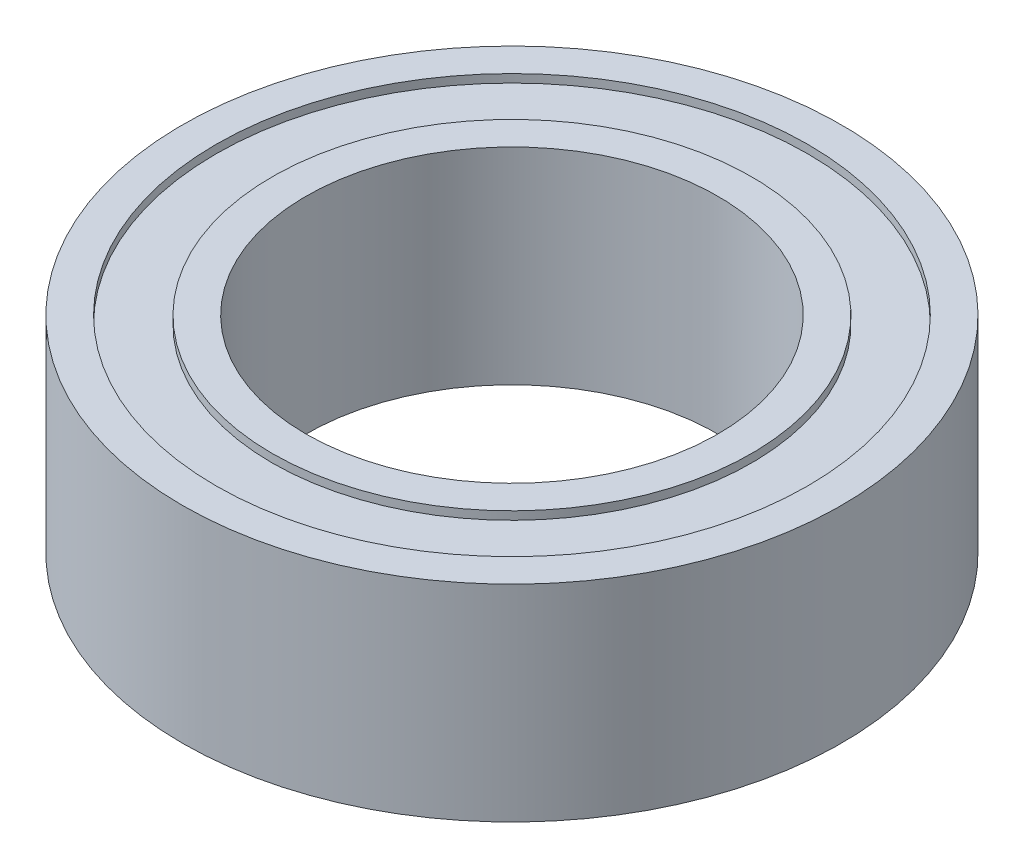
SolidWorks part; units mm, degrees
ref_plane "Front Plane" through (0, 0, 0) normal (0, 0, 1) x (1, 0, 0)
ref_plane "Top Plane" through (0, 0, 0) normal (0, 1, 0) x (1, 0, 0)
ref_plane "Right Plane" through (0, 0, 0) normal (1, 0, 0) x (0, 0, -1)
sketch "Sketch1" plane through (0, 0, 0) normal (0, 1, 0) x (1, 0, 0)
  circle A0 centre (0, 0) radius 4
  circle A1 centre (0, 0) radius 2.5
  dimension "D1" = 8
  dimension "D2" = 5
extrude "Boss-Extrude1" add sketch "Sketch1" along normal blind 1.25
sketch "Sketch2" plane through (0, 1.25, 0) normal (0, 1, 0) x (1, 0, 0)
  line L0 (0, 2.9092) -> (0, 2.5) construction
  line L1 (0, 3.5908) -> (0, 4) construction
  circle A0 centre (0, 0) radius 3.5908
  circle A1 centre (0, 0) radius 2.9092
  circle A2 centre (0, 0) radius 2.5 construction
  circle A3 centre (0, 0) radius 4 construction
extrude "Cut-Extrude1" cut sketch "Sketch2" against normal blind 0.1
mirror "Mirror1" about plane through (0, 0, 0) normal (0, 1, 0) of bodies 104
